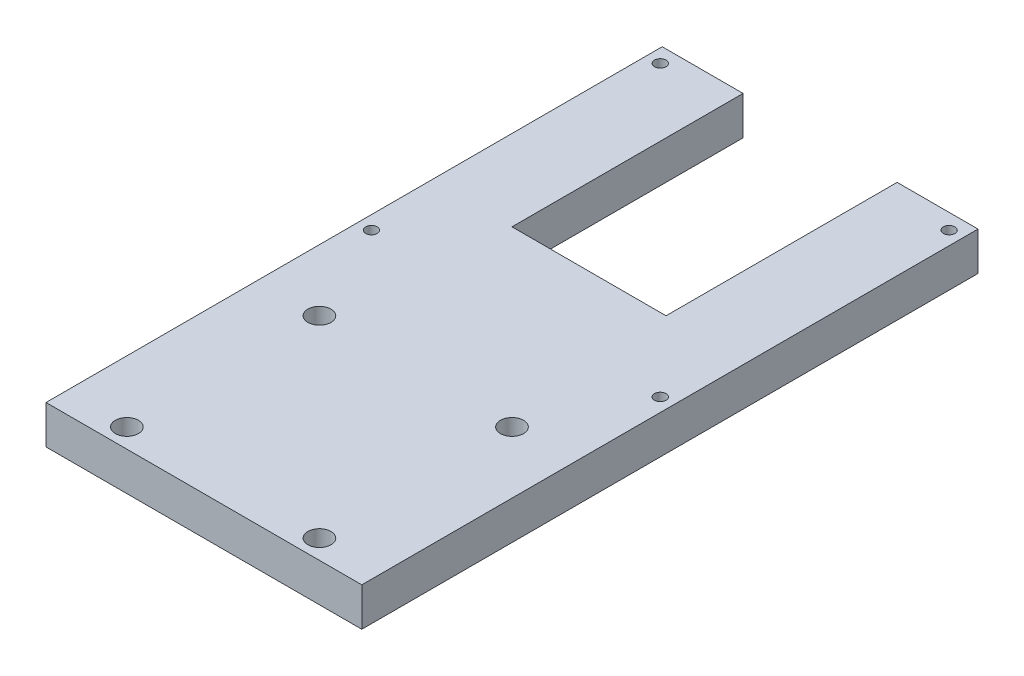
SolidWorks part; units mm, degrees
ref_plane "Front Plane" through (0, 0, 0) normal (0, 0, 1) x (1, 0, 0)
ref_plane "Top Plane" through (0, 0, 0) normal (0, 1, 0) x (1, 0, 0)
ref_plane "Right Plane" through (0, 0, 0) normal (1, 0, 0) x (0, 0, -1)
sketch "Sketch1" plane through (0, 0, 0) normal (0, 1, 0) x (1, 0, 0)
  line L0 (-33.0308, -9.7441) -> (16.9692, -9.7441) construction
  line L1 (32.9692, -64.7441) -> (-49.0308, -64.7441)
  line L2 (32.9692, -64.7441) -> (32.9692, 95.2559)
  line L3 (32.9692, 95.2559) -> (11.9692, 95.2559)
  line L4 (-49.0308, -64.7441) -> (-49.0308, 95.2559)
  line L5 (-45.5308, 16.2559) -> (29.4692, 16.2559) construction
  line L6 (-28.0308, 95.2559) -> (-49.0308, 95.2559)
  line L8 (-28.0308, 95.2559) -> (-28.0308, 35.2559)
  line L9 (-28.0308, 35.2559) -> (11.9692, 35.2559)
  line L10 (11.9692, 95.2559) -> (11.9692, 35.2559)
  circle A0 centre (-33.0308, -59.7441) radius 3
  circle A1 centre (16.9692, -59.7441) radius 3
  circle A2 centre (16.9692, -9.7441) radius 3
  circle A3 centre (-33.0308, -9.7441) radius 3
  circle A4 centre (-45.5308, 91.2559) radius 1.5
  circle A5 centre (29.4692, 91.2559) radius 1.5
  circle A6 centre (29.4692, 16.2559) radius 1.5
  circle A7 centre (-45.5308, 16.2559) radius 1.5
  point P6 (-8.0308, -9.7441)
  point P7 (-8.0308, -64.7441)
  point P16 (-8.0308, 16.2559)
  point P28 (-8.0308, 35.2559)
  dimension "D3" = 6
  dimension "D8" = 50
  dimension "D9" = 5
  dimension "D10" = 3
  dimension "D1" = 160
  dimension "D2" = 82
  dimension "D6" = 16
  dimension "D7" = 50
  dimension "D13" = 4
  dimension "D14" = 40
  dimension "D15" = 60
  dimension "D4" = 2
  dimension "D5" = 2
  dimension "D11" = 2
  dimension "D12" = 2
extrude "Boss-Extrude1" add sketch "Sketch1" along normal blind 10
